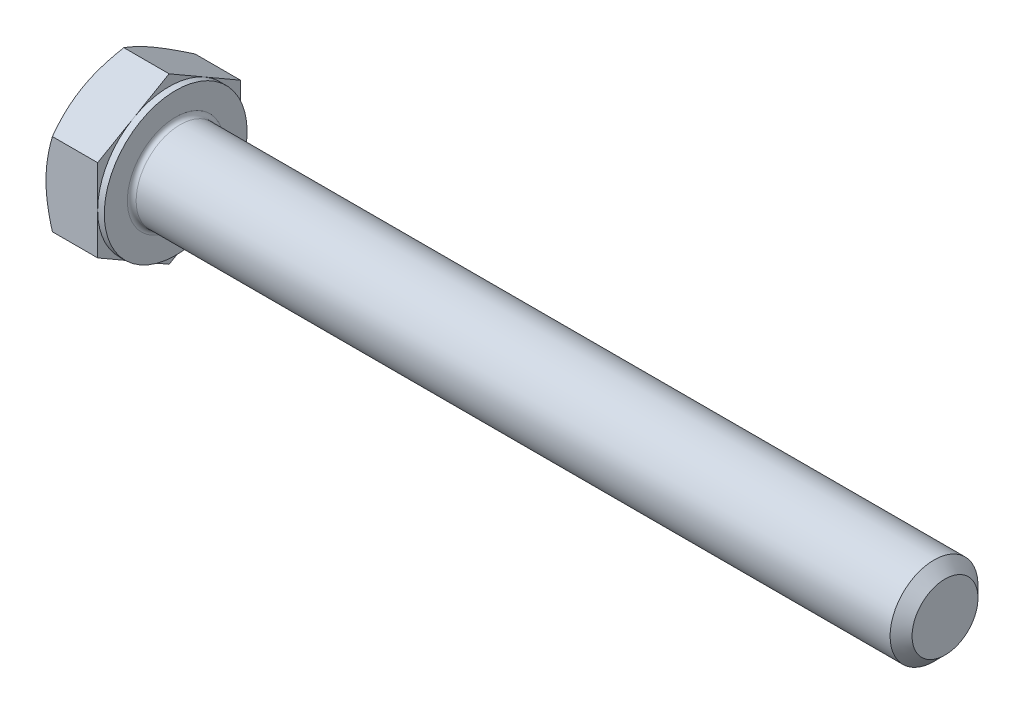
SolidWorks part; units mm, degrees
extrude "基体-拉伸" add sketch "草图1" along normal blind 5.3
sketch "草图1" plane through (0, 0, 0) normal (1, 0, 0) x (0, 0, -1)
  line L0 (6.5, 3.7528) -> (6.5, -3.7528)
  line L1 (-6.5, 3.7528) -> (-6.5, -3.7528)
  line L2 (6.5, -3.7528) -> (0, -7.5056)
  line L3 (0, -7.5056) -> (-6.5, -3.7528)
  line L4 (6.5, 3.7528) -> (0, 7.5056)
  line L5 (0, 7.5056) -> (-6.5, 3.7528)
  dimension "s" = 13
  dimension "D2" = 120
  dimension "D3" = 6.5
  dimension "D4" = 6.5
  dimension "D5" = 6.5
revolve "切除-旋转1" cut sketch "草图3" angle 360 about L6
sketch "草图3" plane through (0, 0, 0) normal (0, 0, 1) x (1, 0, 0)
  line L0 (0, 6.5) -> (3.4673, 12.5056)
  line L1 (0, 7.5056) -> (0, 3.7528) construction
  line L2 (3.4673, 12.5056) -> (3.4673, 17.5056)
  line L3 (3.4673, 17.5056) -> (-10, 17.5056)
  line L4 (-10, 17.5056) -> (-10, 6.5)
  line L5 (-10, 6.5) -> (0, 6.5)
  line L6 (0, 0) -> (99.06, 0) construction
  line L7 (5.3, 7.5056) -> (0, 7.5056) construction
  dimension "D1" = 6.5
  dimension "D2" = 5
  dimension "D3" = 10
  dimension "D4" = 5
  dimension "Head_ch_ang" = 30
material "3.6级"
ref_plane "前视" through (0, 0, 0) normal (0, 0, 1) x (1, 0, 0)
ref_plane "上视" through (0, 0, 0) normal (0, 1, 0) x (1, 0, 0)
ref_plane "右视" through (0, 0, 0) normal (1, 0, 0) x (0, 0, -1)
sketch "草图2" plane through (0, 0, 0) normal (0, 0, 1) x (1, 0, 0)
  line L0 (0, 3.7528) -> (0, -3.7528) construction
  line L1 (0, 0) -> (75.3, 0)
  line L2 (0, 0) -> (0, 4)
  line L3 (0, 4) -> (27.8072, 4)
  line L4 (75.3, 0) -> (75.3, 2.9175)
  line L5 (5.3, 7.5056) -> (5.3, 3.7528) construction
  line L7 (0, 0) -> (96.52, 0) construction
  line L8 (75.3, -2.9175) -> (27.8072, -4) construction
  line L9 (0, -4) -> (27.8072, -4) construction
  line L10 (6.55, 15.24) -> (6.55, -1.27) construction
  line L11 (53.3, 15.24) -> (53.3, -1.27) construction
  line L12 (5.3, 3.7528) -> (5.3, -3.7528) construction
  line L13 (27.8072, 4) -> (75.3, 4)
  line L14 (75.3, 4) -> (75.3, 2.9175)
revolve "凸台-旋转1" add sketch "草图2" angle 360 about L7
cosmetic thread "螺旋线1" parameters "Thread_length"=22, "Thread_minor"=5.835
sketch "草图5" plane through (0, 0, 0) normal (0, 0, 1) x (1, 0, 0)
  line L0 (5.3, 6.5) -> (1.8327, 12.5056)
  line L1 (5.3, 7.5056) -> (5.3, 3.7528) construction
  line L2 (1.8327, 12.5056) -> (1.8327, 17.5056)
  line L3 (1.8327, 17.5056) -> (11.8327, 17.5056)
  line L4 (11.8327, 17.5056) -> (11.8327, 6.5)
  line L5 (11.8327, 6.5) -> (5.3, 6.5)
  line L7 (5.3, 7.5056) -> (0.5806, 7.5056) construction
  line L8 (0, 0) -> (99.06, 0) construction
  line L9 (0, 0) -> (99.06, 0) construction
  dimension "D1" = 6.5
  dimension "D2" = 5
  dimension "D3" = 10
  dimension "D4" = 5
  dimension "Head_ch_ang" = 30
revolve "切除-旋转2" cut sketch "草图5" angle 360 about L8
sketch "草图4" plane through (0, 0, 0) normal (0, 0, 1) x (1, 0, 0)
  line L1 (5.3, 7.5056) -> (5.3, 3.7528) construction
  line L2 (5.3, 6.5) -> (4.7, 6.5)
  line L3 (5.3, 6.5) -> (5.3, 17.5056)
  line L4 (5.3, 17.5056) -> (4.7, 17.5056)
  line L5 (0, 0) -> (95.25, 0) construction
  line L6 (0, 0) -> (96.52, 0) construction
  line L7 (4.7, 6.5) -> (4.7, 17.5056)
  line L8 (4.7194, 7.5056) -> (0.5806, 7.5056) construction
  dimension "D2" = 10
  dimension "D1" = 13
revolve "切除-旋转3" cut sketch "草图4" angle 360 about L5
chamfer "倒角" distance 1 angle 45 1 edges at (75.3, 0, 4)
fillet "圆角" radius 0.4 1 edges at (5.3, 0, -4)
sketch "草图6" plane through (0, 0, 0) normal (0, 0, 1) x (1, 0, 0)
  line L0 (53.3, -2.9175) -> (52.675, -4)
  line L1 (53.3, -2.9175) -> (53.925, -4)
  line L2 (53.925, -4) -> (53.925, -5)
  line L3 (-3.175, 0) -> (5.1513, 0) construction
  line L5 (53.925, -5) -> (52.675, -5)
  line L6 (52.675, -5) -> (52.675, -4)
  dimension "Thread_minor" = 5.835
  dimension "Diameter" = 8
  dimension "Start" = 53.3
revolve "切除-旋转4" [suppressed] cut sketch "草图6" angle 360 about L3
pattern_linear "阵列(线性)1" [suppressed]
equation "\"D3@草图1\" = \"s@草图1\" / 2"
equation "\"D4@草图1\" = \"D3@草图1\""
equation "\"D5@草图1\" = \"D4@草图1\""
equation "\"Thread_minor@螺旋线1\" = \"Minor_dia@草图2\""
equation "\"D1@草图3\" = \"s@草图1\" / 2"
equation "\"D1@草图5\" = \"s@草图1\" / 2"
equation "\"Head_ch_ang@草图5\" = \"Head_ch_ang@草图3\""
equation "\"D1@草图4\" = \"s@草图1\""
equation "\"Thread_length@螺旋线1\" = ((sgn( (\"l@草图2\" - \"p@草图2\" ) - \"h@草图2\" )-1)*( (\"l@草图2\" - \"p@草图2\" ) - \"h@草图2\" ))/-2+ \"h@草图2\""
equation "\"Thread_minor@草图6\" = \"Minor_dia@草图2\""
equation "\"Diameter@草图6\" = \"m@草图2\""
equation "\"Overcut@草图6\" = \"m@草图2\" * 1.25"
equation "\"Start@草图6\" = \"k@基体-拉伸\" + \"l@草图2\" - \"Thread_length@螺旋线1\"  '---Non-countersunk---"
equation "\"Num_threads@阵列(线性)1\" = int( \"Thread_length@螺旋线1\" / \"p@草图2\" + 0.999 )  + 1"
equation "\"Advance@阵列(线性)1\" = \"Thread_length@螺旋线1\" /  (\"Num_threads@阵列(线性)1\" - 1) 'relax it"
equation "\"Num_threads@阵列(线性)1\" = \"Num_threads@阵列(线性)1\" - sgn( \"Num_threads@阵列(线性)1\" - 1) '---chamfered tips only---"
equation "\"Minor_dia@草图2\" = \"m@草图2\"-\"p@草图2\" * 1.732"
equation "\"D1@倒角\" = \"p@草图2\"*0.8"
